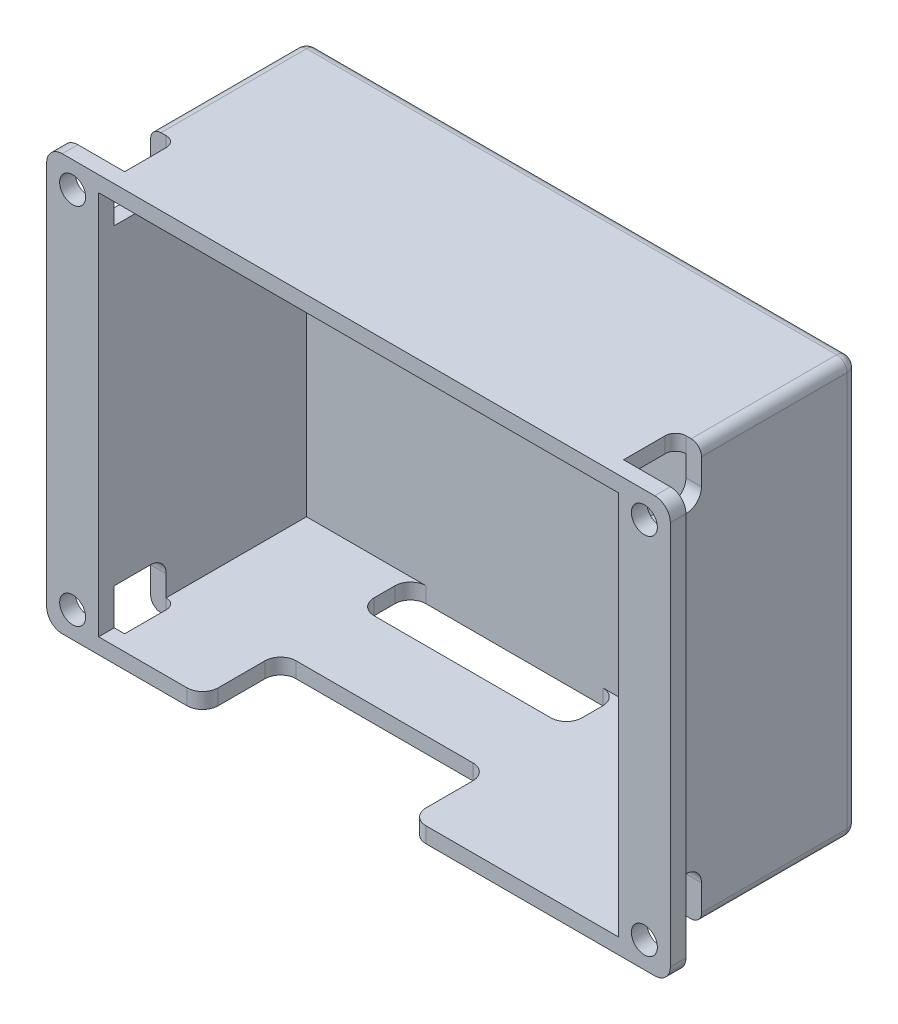
SolidWorks part; units mm, degrees
ref_plane "Front Plane" through (0, 0, 0) normal (0, 0, 1) x (1, 0, 0)
ref_plane "Top Plane" through (0, 0, 0) normal (0, 1, 0) x (1, 0, 0)
ref_plane "Right Plane" through (0, 0, 0) normal (1, 0, 0) x (0, 0, -1)
sketch "Sketch2" plane through (0, 0, 0) normal (0, 0, 1) x (1, 0, 0)
  line L1 (15.306, 62.8336) -> (75.306, 62.8336)
  line L2 (15.306, 62.8336) -> (15.306, 22.8336)
  line L3 (15.306, 22.8336) -> (75.306, 22.8336)
  line L4 (75.306, 62.8336) -> (75.306, 22.8336)
  circle A0 centre (17.806, 60.3336) radius 1.25
  circle A1 centre (17.806, 25.3336) radius 1.25
  circle A2 centre (72.806, 25.3336) radius 1.25
  circle A3 centre (72.806, 60.3336) radius 1.25
  dimension "D2" = 2.5
  dimension "D1" = 60
  dimension "D3" = 40
  dimension "D4" = 2.5
  dimension "D5" = 2.5
  dimension "D6" = 2.5
  dimension "D7" = 2.5
extrude "Boss-Extrude3" add sketch "Sketch2" along normal blind 1.5
sketch "Sketch3" plane through (0, 0, 0) normal (0, 0, -1) x (-1, 0, 0)
  line L0 (-75.306, 62.8336) -> (-15.306, 62.8336) construction
  line L1 (-71.806, 62.8336) -> (-18.806, 62.8336)
  line L2 (-71.806, 62.8336) -> (-71.806, 22.8336)
  line L3 (-71.806, 22.8336) -> (-18.806, 22.8336)
  line L4 (-18.806, 62.8336) -> (-18.806, 22.8336)
  line L6 (-15.306, 22.8336) -> (-75.306, 22.8336) construction
  line L7 (-75.306, 22.8336) -> (-75.306, 62.8336) construction
  line L8 (-15.306, 62.8336) -> (-15.306, 22.8336) construction
  dimension "D1" = 0
  dimension "D2" = 0
  dimension "D3" = 3.5
  dimension "D4" = 3.5
extrude "Boss-Extrude4" add sketch "Sketch3" along normal blind 20
sketch "Sketch7" plane through (0, 0, 1.5) normal (0, 0, 1) x (1, 0, 0)
  line L0 (75.306, 62.8336) -> (15.306, 62.8336) construction
  line L1 (20.306, 61.3336) -> (70.306, 61.3336)
  line L2 (20.306, 61.3336) -> (20.306, 24.3336)
  line L3 (20.306, 24.3336) -> (70.306, 24.3336)
  line L4 (70.306, 61.3336) -> (70.306, 24.3336)
  line L5 (15.306, 62.8336) -> (15.306, 22.8336) construction
  line L6 (75.306, 22.8336) -> (75.306, 62.8336) construction
  line L7 (15.306, 22.8336) -> (75.306, 22.8336) construction
  dimension "D1" = 1.5
  dimension "D2" = 5
  dimension "D3" = 5
  dimension "D4" = 1.5
extrude "Cut-Extrude4" cut sketch "Sketch7" against normal blind 20
sketch "Sketch11" plane through (18.806, 0, 0) normal (-1, 0, 0) x (0, 0, 1)
  line L1 (0, 62.8336) -> (-5, 62.8336)
  line L2 (0, 62.8336) -> (0, 57.8336)
  line L3 (0, 57.8336) -> (-5, 57.8336)
  line L4 (-5, 62.8336) -> (-5, 57.8336)
  line L5 (0, 22.8336) -> (-5, 22.8336)
  line L6 (0, 22.8336) -> (0, 27.8336)
  line L7 (0, 27.8336) -> (-5, 27.8336)
  line L8 (-5, 22.8336) -> (-5, 27.8336)
  dimension "D1" = 5
  dimension "D2" = 5
extrude "Cut-Extrude8" cut sketch "Sketch11" against normal blind 2.5
sketch "Sketch12" plane through (71.806, 0, 0) normal (1, 0, 0) x (0, 0, -1)
  line L1 (0, 62.8336) -> (5, 62.8336)
  line L2 (0, 62.8336) -> (0, 57.8336)
  line L3 (0, 57.8336) -> (5, 57.8336)
  line L4 (5, 62.8336) -> (5, 57.8336)
  line L5 (0, 22.8336) -> (5, 22.8336)
  line L6 (0, 22.8336) -> (0, 27.8336)
  line L7 (0, 27.8336) -> (5, 27.8336)
  line L8 (5, 22.8336) -> (5, 27.8336)
  dimension "D1" = 5
  dimension "D2" = 5
extrude "Cut-Extrude9" cut sketch "Sketch12" against normal blind 2.5
sketch "Sketch15" plane through (0, 22.8336, 0) normal (0, -1, 0) x (1, 0, 0)
  line L0 (15.306, 1.5) -> (75.306, 1.5) construction
  line L1 (50.306, 1.5) -> (30.306, 1.5)
  line L2 (50.306, 1.5) -> (50.306, -6)
  line L3 (50.306, -6) -> (30.306, -6)
  line L4 (30.306, 1.5) -> (30.306, -6)
  line L6 (71.806, -20) -> (18.806, -20) construction
  line L7 (50.306, -18.5) -> (30.306, -18.5)
  line L8 (50.306, -18.5) -> (50.306, -13.5)
  line L9 (50.306, -13.5) -> (30.306, -13.5)
  line L10 (30.306, -18.5) -> (30.306, -13.5)
  line L11 (15.306, 1.5) -> (15.306, 0) construction
  dimension "D1" = 15
  dimension "D2" = 35
  dimension "D3" = 7.5
  dimension "D4" = 1.5
  dimension "D5" = 5
extrude "Cut-Extrude11" cut sketch "Sketch15" against normal blind 5
fillet "Fillet6" radius 1.5 16 edges at (30.306, 23.5836, -13.5) (50.306, 23.5836, -13.5) (50.306, 23.5836, -6) (50.306, 23.5836, -18.5) (30.306, 23.5836, -18.5) (50.306, 23.5836, 1.5) (30.306, 23.5836, -6) (30.306, 23.5836, 1.5) (71.056, 27.8336, -5) (71.056, 57.8336, -5) (19.556, 57.8336, -5) (19.556, 27.8336, -5) (75.306, 22.8336, 0.75) (75.306, 62.8336, 0.75) (15.306, 22.8336, 0.75) (15.306, 62.8336, 0.75)
fillet "Fillet7" radius 1 12 edges at (45.306, 62.8336, -20) (18.806, 42.8336, -20) (45.306, 22.8336, -20) (71.806, 42.8336, -20) (21.306, 23.5836, -5) (69.306, 23.5836, -5) (69.306, 62.0836, -5) (21.306, 62.0836, -5) (71.806, 62.8336, -12.5) (18.806, 62.8336, -12.5) (71.806, 22.8336, -12.5) (18.806, 22.8336, -12.5)
